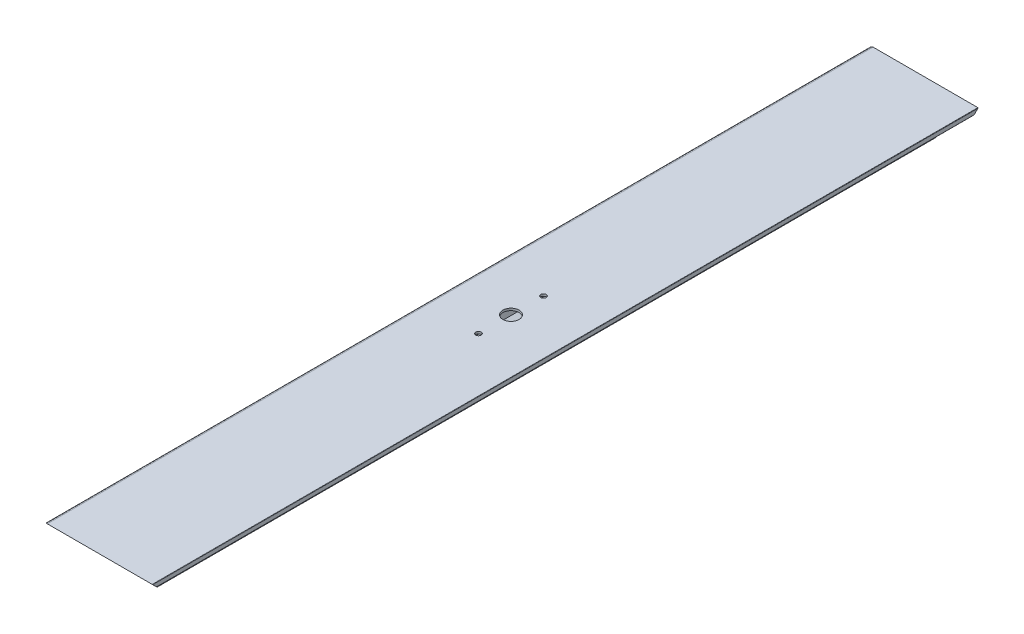
SolidWorks part; units mm, degrees
ref_plane "Front Plane" through (0, 0, 0) normal (0, 0, 1) x (1, 0, 0)
ref_plane "Top Plane" through (0, 0, 0) normal (0, 1, 0) x (1, 0, 0)
ref_plane "Right Plane" through (0, 0, 0) normal (1, 0, 0) x (0, 0, -1)
sketch "Model" plane through (0, 0, 0) normal (0, 0, 1) x (1, 0, 0)
  line L0 (-162.8727, 78.9684) -> (-162.8727, 75.3684)
  line L1 (-97.198, 332.0635) -> (-96.4981, 340.0635)
  line L2 (-92.6351, 332.0635) -> (-97.198, 332.0635)
  line L3 (-97.1625, 332.4695) -> (-95.9741, 333.6579)
  line L4 (-97.0676, 333.5543) -> (-95.8792, 334.7427)
  line L5 (-96.9727, 334.6392) -> (-95.0062, 336.6057)
  line L6 (-96.8777, 335.7241) -> (-95.6894, 336.9124)
  line L7 (-96.7828, 336.8089) -> (-95.5945, 337.9973)
  line L8 (-96.6879, 337.8938) -> (-94.5182, 340.0635)
  line L9 (-120.185, 95.3464) -> (20.315, 95.3464)
  line L10 (20.315, 85.3464) -> (-120.185, 85.3464)
  line L11 (-173.435, 75.3464) -> (20.315, 75.3464)
  line L12 (20.315, 105.3464) -> (-173.435, 105.3464)
  line L13 (-173.435, 342.7864) -> (20.315, 342.7864)
  line L14 (20.315, 85.0964) -> (-120.185, 85.0964)
  line L15 (-120.185, 95.0964) -> (20.315, 95.0964)
  line L16 (-120.185, 105.0964) -> (20.315, 105.0964)
  line L17 (-173.435, 330.0364) -> (20.315, 330.0364)
  line L18 (-82.355, 62.0364) -> (-173.435, 62.0364)
  line L19 (-82.355, 75.0964) -> (-173.435, 75.0964)
  line L20 (-173.435, 62.0364) -> (-173.435, 342.7864)
  line L21 (-173.435, 105.0964) -> (-120.185, 105.0964)
  line L22 (-120.435, 105.3464) -> (-120.435, 75.0964)
  line L23 (-120.185, 95.0964) -> (-120.185, 85.0964)
  line L24 (-120.185, 85.0964) -> (-120.185, 75.0964)
  line L25 (-120.185, 105.0964) -> (-120.185, 95.0964)
  line L26 (-135.8829, 332.0772) -> (-133.6922, 334.2679)
  line L27 (-136.8281, 332.122) -> (-135.9914, 332.9587)
  line L28 (-138.513, 334.4856) -> (-137.6233, 334.4856)
  line L29 (-138.0471, 332.8829) -> (-137.3837, 333.5463)
  line L30 (-138.3972, 333.5227) -> (-137.6286, 334.2914)
  line L31 (-137.8451, 337.0447) -> (-137.151, 337.7388)
  line L32 (-138.0802, 337.7995) -> (-135.8255, 340.0542)
  line L33 (-138.5201, 334.3898) -> (-138.4243, 334.4856)
  line L34 (-134.4764, 338.4335) -> (-133.7983, 339.1117)
  line L35 (-134.9397, 338.9602) -> (-134.2749, 339.6249)
  line L36 (-135.3098, 335.4283) -> (-137.1787, 336.4102)
  line L37 (-136.7085, 337.2046) -> (-134.8554, 336.2311)
  line L38 (-136.0846, 335.8354) -> (-135.4018, 336.5182)
  line L39 (-136.0607, 332.9602) -> (-136.0367, 332.9596)
  line L40 (-136.0968, 332.9586) -> (-136.0607, 332.9602)
  line L41 (-137.5265, 332.4136) -> (-136.8485, 333.0915)
  line L42 (-136.7336, 336.1763) -> (-136.0508, 336.8591)
  line L43 (-137.3711, 336.5287) -> (-136.6998, 337.2)
  line L44 (-135.2783, 335.4135) -> (-135.3098, 335.4283)
  line L45 (-133.4601, 337.7152) -> (-134.3499, 337.7152)
  line L46 (-134.5809, 334.3692) -> (-133.8142, 335.1359)
  line L47 (-134.8458, 335.0942) -> (-134.1871, 335.7529)
  line L48 (-135.4356, 335.4944) -> (-134.7486, 336.1814)
  line L49 (-134.2047, 337.7152) -> (-133.5051, 338.4148)
  line L50 (-135.7157, 339.1741) -> (-134.9284, 339.9614)
  line L51 (-136.0196, 339.1378) -> (-136.079, 339.1324)
  line L52 (-135.9604, 339.1472) -> (-136.0196, 339.1378)
  line L53 (-107.3609, 332.0635) -> (-106.661, 340.0635)
  line L54 (-106.0574, 334.5678) -> (-106.2765, 332.0635)
  line L55 (-102.5158, 332.0635) -> (-104.0259, 334.5678)
  line L56 (-102.7955, 334.7127) -> (-101.198, 332.0635)
  line L57 (-117.9979, 332.0635) -> (-117.298, 340.0635)
  line L58 (-116.611, 335.5213) -> (-116.9135, 332.0635)
  line L59 (-112.4453, 332.0635) -> (-112.1428, 335.5213)
  line L60 (-110.661, 340.0635) -> (-111.3609, 332.0635)
  line L61 (-101.7917, 332.0635) -> (-101.4213, 332.4339)
  line L62 (-102.6158, 332.2294) -> (-101.7937, 333.0514)
  line L63 (-106.7414, 332.0635) -> (-106.232, 332.573)
  line L64 (-124.9402, 332.1742) -> (-121.9937, 335.1207)
  line L65 (-126.0381, 332.0663) -> (-124.7819, 333.3225)
  line L66 (-126.8973, 332.197) -> (-125.9425, 333.1518)
  line L67 (-112.4287, 332.0635) -> (-111.2586, 333.2336)
  line L68 (-117.3784, 332.0635) -> (-116.869, 332.573)
  line L69 (-116.9135, 332.0635) -> (-117.9979, 332.0635)
  line L70 (-111.3609, 332.0635) -> (-112.4453, 332.0635)
  line L71 (-111.4387, 332.0635) -> (-111.3535, 332.1488)
  line L72 (-106.2765, 332.0635) -> (-107.3609, 332.0635)
  line L73 (-101.198, 332.0635) -> (-102.5158, 332.0635)
  line L74 (-116.5161, 336.6057) -> (-112.048, 336.6057)
  line L75 (-112.1428, 335.5213) -> (-116.611, 335.5213)
  line L76 (-115.9005, 335.5213) -> (-114.8161, 336.6057)
  line L77 (-124.2639, 338.7902) -> (-123.4199, 339.6342)
  line L78 (-128.7127, 333.3515) -> (-127.9075, 334.1566)
  line L79 (-129.112, 333.9421) -> (-128.2679, 334.7862)
  line L80 (-129.3993, 334.6447) -> (-128.4536, 335.5904)
  line L81 (-129.5441, 335.4898) -> (-128.3208, 336.7132)
  line L82 (-129.46, 336.564) -> (-126.0538, 339.9701)
  line L83 (-125.0722, 338.9718) -> (-124.1269, 339.9172)
  line L84 (-126.1994, 338.8346) -> (-124.9757, 340.0583)
  line L85 (-127.6117, 332.4726) -> (-126.7637, 333.3205)
  line L86 (-128.2122, 332.8619) -> (-127.4061, 333.668)
  line L87 (-123.6305, 338.4336) -> (-122.8256, 339.2386)
  line L88 (-122.8588, 335.1207) -> (-121.7305, 335.1207)
  line L89 (-121.5655, 337.0064) -> (-122.6938, 337.0064)
  line L90 (-122.0879, 337.0064) -> (-121.6581, 337.4362)
  line L91 (-122.786, 337.2982) -> (-121.938, 338.1462)
  line L92 (-123.1373, 337.9369) -> (-122.3311, 338.7431)
  line L93 (-116.2136, 340.0635) -> (-116.5161, 336.6057)
  line L94 (-117.4879, 337.8938) -> (-116.2995, 339.0822)
  line L95 (-117.3929, 338.9787) -> (-116.3081, 340.0635)
  line L96 (-117.9624, 332.4695) -> (-116.774, 333.6579)
  line L97 (-117.8675, 333.5543) -> (-116.6791, 334.7427)
  line L98 (-117.7726, 334.6392) -> (-115.8061, 336.6057)
  line L99 (-117.6777, 335.7241) -> (-116.4893, 336.9124)
  line L100 (-117.5828, 336.8089) -> (-116.3944, 337.9973)
  line L101 (-117.298, 340.0635) -> (-116.2136, 340.0635)
  line L102 (-105.6715, 338.9791) -> (-105.9639, 335.6368)
  line L103 (-105.9639, 335.6368) -> (-103.6409, 335.6368)
  line L104 (-104.0259, 334.5678) -> (-106.0574, 334.5678)
  line L105 (-106.661, 340.0635) -> (-103.2536, 340.0635)
  line L106 (-107.2305, 333.5543) -> (-105.1481, 335.6368)
  line L107 (-106.9458, 336.8089) -> (-105.7574, 337.9973)
  line L108 (-106.8509, 337.8938) -> (-104.6812, 340.0635)
  line L109 (-106.7559, 338.9787) -> (-105.6711, 340.0635)
  line L110 (-112.048, 336.6057) -> (-111.7454, 340.0635)
  line L111 (-111.8775, 338.5544) -> (-110.6891, 339.7428)
  line L112 (-112.9307, 335.5213) -> (-110.8789, 337.5731)
  line L113 (-113.9206, 335.5213) -> (-112.8362, 336.6057)
  line L114 (-114.9106, 335.5213) -> (-113.8262, 336.6057)
  line L115 (-112.352, 333.1301) -> (-111.1637, 334.3185)
  line L116 (-112.2571, 334.215) -> (-111.0687, 335.4034)
  line L117 (-112.1622, 335.2999) -> (-110.9738, 336.4882)
  line L118 (-111.9724, 337.4696) -> (-110.784, 338.658)
  line L119 (-111.7454, 340.0635) -> (-110.661, 340.0635)
  line L120 (-111.7825, 339.6393) -> (-111.3583, 340.0635)
  line L121 (-107.3254, 332.4695) -> (-106.1371, 333.6579)
  line L122 (-107.1356, 334.6392) -> (-105.9472, 335.8276)
  line L123 (-107.0407, 335.7241) -> (-105.8523, 336.9124)
  line L124 (-103.733, 334.082) -> (-100.7764, 337.0386)
  line L125 (-101.9127, 336.8923) -> (-100.7724, 338.0326)
  line L126 (-101.8837, 337.9112) -> (-101.029, 338.7659)
  line L127 (-102.2514, 338.5335) -> (-101.4504, 339.3345)
  line L128 (-102.8681, 338.9067) -> (-102.0179, 339.7569)
  line L129 (-103.7857, 338.9791) -> (-102.748, 340.0168)
  line L130 (-104.7756, 338.9791) -> (-103.6912, 340.0635)
  line L131 (-103.3485, 338.9791) -> (-105.6715, 338.9791)
  line L132 (-104.2371, 334.5678) -> (-103.0712, 335.7337)
  line L133 (-105.2271, 334.5678) -> (-104.1581, 335.6368)
  line L134 (-102.9882, 332.8469) -> (-102.1661, 333.669)
  line L135 (-103.3606, 333.4645) -> (-102.5385, 334.2865)
  line L136 (20.315, 342.7864) -> (20.315, 62.0364)
  line L137 (20.315, 62.0364) -> (-82.355, 62.0364)
  line L138 (-82.355, 75.0964) -> (20.315, 75.0964)
  line L139 (-33.435, 105.0964) -> (-33.435, 62.0364)
  line L140 (-76.935, 105.0964) -> (-76.935, 62.0364)
  line L141 (-76.685, 62.0364) -> (-76.685, 75.0964)
  line L142 (-33.185, 62.0364) -> (-33.185, 95.0964)
  line L143 (-76.685, 95.0964) -> (-76.685, 75.0964)
  line L144 (-76.685, 95.0964) -> (-76.685, 105.0964)
  line L145 (-33.185, 95.0964) -> (-33.185, 105.0964)
  line L146 (-69.6745, 332.0635) -> (-68.9746, 340.0635)
  line L147 (-68.371, 334.5678) -> (-68.5901, 332.0635)
  line L148 (-64.8294, 332.0635) -> (-66.3395, 334.5678)
  line L149 (-65.1091, 334.7127) -> (-63.5116, 332.0635)
  line L150 (-78.2374, 332.0635) -> (-77.5375, 340.0635)
  line L151 (-73.5796, 333.1479) -> (-73.6745, 332.0635)
  line L152 (-88.6351, 332.0635) -> (-87.9352, 340.0635)
  line L153 (-87.1624, 336.5009) -> (-87.5507, 332.0635)
  line L154 (-86.0396, 332.0635) -> (-87.1624, 336.5009)
  line L155 (-82.9336, 336.5009) -> (-84.8329, 332.0635)
  line L156 (-83.3218, 332.0635) -> (-82.9336, 336.5009)
  line L157 (-81.5375, 340.0635) -> (-82.2374, 332.0635)
  line L158 (-92.5402, 333.1479) -> (-92.6351, 332.0635)
  line L159 (-64.1052, 332.0635) -> (-63.7349, 332.4339)
  line L160 (-64.9294, 332.2294) -> (-64.1073, 333.0514)
  line L161 (-69.055, 332.0635) -> (-68.5455, 332.573)
  line L162 (-93.6086, 332.0635) -> (-92.5417, 333.1304)
  line L163 (-94.5986, 332.0635) -> (-93.5142, 333.1479)
  line L164 (-95.5885, 332.0635) -> (-94.5041, 333.1479)
  line L165 (-96.5785, 332.0635) -> (-95.4941, 333.1479)
  line L166 (-74.6481, 332.0635) -> (-73.5811, 333.1304)
  line L167 (-75.638, 332.0635) -> (-74.5536, 333.1479)
  line L168 (-76.628, 332.0635) -> (-75.5436, 333.1479)
  line L169 (-77.6179, 332.0635) -> (-76.5335, 333.1479)
  line L170 (-83.0658, 332.0635) -> (-82.158, 332.9713)
  line L171 (-85.0457, 332.0635) -> (-84.6736, 332.4356)
  line L172 (-86.0357, 332.0635) -> (-83.9328, 334.1664)
  line L173 (-88.0156, 332.0635) -> (-87.5061, 332.573)
  line L174 (-87.5507, 332.0635) -> (-88.6351, 332.0635)
  line L175 (-82.2374, 332.0635) -> (-83.3218, 332.0635)
  line L176 (-84.8329, 332.0635) -> (-86.0396, 332.0635)
  line L177 (-68.5901, 332.0635) -> (-69.6745, 332.0635)
  line L178 (-73.6745, 332.0635) -> (-78.2374, 332.0635)
  line L179 (-63.5116, 332.0635) -> (-64.8294, 332.0635)
  line L180 (-87.9352, 340.0635) -> (-86.9184, 340.0635)
  line L181 (-88.5995, 332.4695) -> (-87.4112, 333.6579)
  line L182 (-88.5046, 333.5543) -> (-87.3163, 334.7427)
  line L183 (-88.4097, 334.6392) -> (-87.2213, 335.8276)
  line L184 (-88.3148, 335.7241) -> (-86.3241, 337.7148)
  line L185 (-88.2199, 336.8089) -> (-86.524, 338.5048)
  line L186 (-88.125, 337.8938) -> (-86.7239, 339.2949)
  line L187 (-88.0301, 338.9787) -> (-86.9452, 340.0635)
  line L188 (-92.03, 338.9791) -> (-95.5086, 338.9791)
  line L189 (-96.4981, 340.0635) -> (-91.9352, 340.0635)
  line L190 (-92.6327, 338.9791) -> (-91.9722, 339.6396)
  line L191 (-93.6227, 338.9791) -> (-92.5383, 340.0635)
  line L192 (-94.6126, 338.9791) -> (-93.5282, 340.0635)
  line L193 (-96.593, 338.9787) -> (-95.5081, 340.0635)
  line L194 (-96.0187, 333.1479) -> (-92.5402, 333.1479)
  line L195 (-92.3325, 335.5213) -> (-95.8111, 335.5213)
  line L196 (-95.7162, 336.6057) -> (-92.2377, 336.6057)
  line L197 (-95.1006, 335.5213) -> (-94.0162, 336.6057)
  line L198 (-95.8111, 335.5213) -> (-96.0187, 333.1479)
  line L199 (-95.5086, 338.9791) -> (-95.7162, 336.6057)
  line L200 (-92.2377, 336.6057) -> (-92.3325, 335.5213)
  line L201 (-93.1207, 335.5213) -> (-92.257, 336.385)
  line L202 (-94.1107, 335.5213) -> (-93.0263, 336.6057)
  line L203 (-91.9352, 340.0635) -> (-92.03, 338.9791)
  line L204 (-85.2969, 333.6557) -> (-82.5543, 340.0635)
  line L205 (-83.2515, 332.8678) -> (-82.0631, 334.0562)
  line L206 (-83.1565, 333.9527) -> (-81.9682, 335.1411)
  line L207 (-83.0616, 335.0376) -> (-81.8733, 336.2259)
  line L208 (-82.9667, 336.1224) -> (-81.7783, 337.3108)
  line L209 (-84.454, 335.6251) -> (-81.6834, 338.3956)
  line L210 (-83.7132, 337.3558) -> (-81.5885, 339.4805)
  line L211 (-82.9724, 339.0866) -> (-81.9955, 340.0635)
  line L212 (-86.9184, 340.0635) -> (-85.2969, 333.6557)
  line L213 (-86.2387, 332.8504) -> (-85.3245, 333.7646)
  line L214 (-86.4386, 333.6405) -> (-85.5244, 334.5547)
  line L215 (-86.6385, 334.4305) -> (-85.7243, 335.3447)
  line L216 (-86.8385, 335.2205) -> (-85.9242, 336.1347)
  line L217 (-87.0384, 336.0106) -> (-86.1242, 336.9248)
  line L218 (-85.1948, 333.8943) -> (-83.192, 335.8971)
  line L219 (-82.5543, 340.0635) -> (-81.5375, 340.0635)
  line L220 (-69.639, 332.4695) -> (-68.4506, 333.6579)
  line L221 (-69.5441, 333.5543) -> (-67.4616, 335.6368)
  line L222 (-69.4491, 334.6392) -> (-68.2608, 335.8276)
  line L223 (-69.3542, 335.7241) -> (-68.1659, 336.9124)
  line L224 (-69.2593, 336.8089) -> (-68.071, 337.9973)
  line L225 (-77.0581, 333.1479) -> (-73.5796, 333.1479)
  line L226 (-73.372, 335.5213) -> (-76.8505, 335.5213)
  line L227 (-76.7556, 336.6057) -> (-73.2771, 336.6057)
  line L228 (-73.0695, 338.9791) -> (-76.548, 338.9791)
  line L229 (-77.5375, 340.0635) -> (-72.9746, 340.0635)
  line L230 (-74.1602, 335.5213) -> (-73.2964, 336.385)
  line L231 (-74.6621, 338.9791) -> (-73.5777, 340.0635)
  line L232 (-75.6521, 338.9791) -> (-74.5677, 340.0635)
  line L233 (-77.7273, 337.8938) -> (-75.5576, 340.0635)
  line L234 (-77.6324, 338.9787) -> (-76.5476, 340.0635)
  line L235 (-76.14, 335.5213) -> (-75.0556, 336.6057)
  line L236 (-78.0121, 334.6392) -> (-76.0456, 336.6057)
  line L237 (-76.8505, 335.5213) -> (-77.0581, 333.1479)
  line L238 (-76.548, 338.9791) -> (-76.7556, 336.6057)
  line L239 (-78.2019, 332.4695) -> (-77.0135, 333.6579)
  line L240 (-78.107, 333.5543) -> (-76.9186, 334.7427)
  line L241 (-77.9172, 335.7241) -> (-76.7288, 336.9124)
  line L242 (-77.8223, 336.8089) -> (-76.6339, 337.9973)
  line L243 (-75.1501, 335.5213) -> (-74.0657, 336.6057)
  line L244 (-72.9746, 340.0635) -> (-73.0695, 338.9791)
  line L245 (-73.6722, 338.9791) -> (-73.0117, 339.6396)
  line L246 (-73.2771, 336.6057) -> (-73.372, 335.5213)
  line L247 (-65.3017, 332.8469) -> (-64.4797, 333.669)
  line L248 (-66.0465, 334.082) -> (-63.0899, 337.0386)
  line L249 (-65.1817, 338.9067) -> (-64.3314, 339.7569)
  line L250 (-66.0992, 338.9791) -> (-65.0615, 340.0168)
  line L251 (-67.0892, 338.9791) -> (-66.0048, 340.0635)
  line L252 (-69.1644, 337.8938) -> (-66.9947, 340.0635)
  line L253 (-69.0695, 338.9787) -> (-67.9846, 340.0635)
  line L254 (-65.6621, 338.9791) -> (-67.9851, 338.9791)
  line L255 (-68.2775, 335.6368) -> (-65.9545, 335.6368)
  line L256 (-66.3395, 334.5678) -> (-68.371, 334.5678)
  line L257 (-67.5406, 334.5678) -> (-66.4717, 335.6368)
  line L258 (-67.9851, 338.9791) -> (-68.2775, 335.6368)
  line L259 (-65.6741, 333.4645) -> (-64.8521, 334.2865)
  line L260 (-66.5507, 334.5678) -> (-65.3848, 335.7337)
  line L261 (-68.9746, 340.0635) -> (-65.5672, 340.0635)
  line L262 (-64.565, 338.5335) -> (-63.7639, 339.3345)
  line L263 (-64.2263, 336.8923) -> (-63.086, 338.0326)
  line L264 (-64.1972, 337.9112) -> (-63.3425, 338.7659)
  line L265 (-33.235, 330.0364) -> (-33.235, 343.0364)
  line L266 (-122.3762, 215.7611) -> (-104.8919, 215.7611)
  line L267 (-104.8919, 215.7611) -> (-94.8762, 221.9241)
  line L268 (-94.8762, 221.9241) -> (-94.8762, 234.4611)
  line L269 (-95.1762, 234.7611) -> (-122.3762, 234.7611)
  line L270 (-123.8762, 233.2611) -> (-123.8762, 217.2611)
  line L271 (-83.3762, 213.7611) -> (-47.8762, 213.7611)
  line L272 (-44.8762, 216.7611) -> (-44.8762, 232.4611)
  line L273 (-44.5762, 232.7611) -> (-28.1762, 232.7611)
  line L274 (-27.8762, 233.0611) -> (-27.8762, 236.4611)
  line L275 (-28.1762, 236.7611) -> (-124.8762, 236.7611)
  line L276 (-127.8762, 233.7611) -> (-127.8762, 216.7611)
  line L277 (-124.8762, 213.7611) -> (-102.4177, 213.7611)
  line L278 (-102.4177, 213.7611) -> (-93.4187, 219.2985)
  line L279 (-93.4187, 219.2985) -> (-83.3762, 213.7611)
  line L280 (-82.8614, 215.7611) -> (-50.8762, 215.7611)
  line L281 (-48.8762, 217.7611) -> (-48.8762, 234.4611)
  line L282 (-49.1762, 234.7611) -> (-92.5762, 234.7611)
  line L283 (-92.8762, 234.4611) -> (-92.8762, 221.2832)
  line L284 (-92.8762, 221.2832) -> (-82.8614, 215.7611)
  arc A0 (-137.8968, 332.7133) -> (-137.2797, 332.2779) centre (-136.3771, 334.2121) ccw
  arc A1 (-136.1303, 332.0696) -> (-134.4439, 332.7179) centre (-136.0797, 334.4557) ccw
  arc A2 (-137.2797, 332.2779) -> (-136.1303, 332.0696) centre (-136.3093, 334.3574) ccw
  arc A3 (-137.4521, 339.4174) -> (-138.0003, 338.5211) centre (-135.946, 337.8806) ccw
  arc A4 (-138.0372, 337.5237) -> (-137.1787, 336.4102) centre (-136.3894, 337.9064) ccw
  arc A5 (-138.0003, 338.5211) -> (-138.0372, 337.5237) centre (-136.1826, 337.9544) ccw
  arc A6 (-138.513, 334.4856) -> (-138.3231, 333.3359) centre (-136.2433, 334.2702) ccw
  arc A7 (-138.3231, 333.3359) -> (-137.8968, 332.7133) centre (-136.381, 334.2083) ccw
  arc A8 (-136.1086, 339.1312) -> (-136.8552, 338.8092) centre (-136.0647, 338.0029) ccw
  arc A9 (-134.7814, 338.8399) -> (-135.2015, 339.09) centre (-135.6424, 337.8715) ccw
  arc A10 (-133.6796, 338.9039) -> (-134.1549, 339.526) centre (-135.521, 337.9895) ccw
  arc A11 (-136.0367, 332.9596) -> (-135.033, 333.3339) centre (-135.9879, 334.3617) ccw
  arc A12 (-136.8315, 333.0836) -> (-136.0968, 332.9586) centre (-136.2282, 334.4081) ccw
  arc A13 (-137.2271, 333.358) -> (-136.8315, 333.0836) centre (-136.2714, 334.3133) ccw
  arc A14 (-137.5008, 333.7533) -> (-137.2271, 333.358) centre (-136.2749, 334.3098) ccw
  arc A15 (-137.6233, 334.4856) -> (-137.5008, 333.7533) centre (-136.1881, 334.3492) ccw
  arc A16 (-137.1671, 337.7985) -> (-136.7085, 337.2046) centre (-136.2881, 338.0032) ccw
  arc A17 (-137.1476, 338.3307) -> (-137.1671, 337.7985) centre (-136.1779, 338.0288) ccw
  arc A18 (-136.8552, 338.8092) -> (-137.1476, 338.3307) centre (-136.0516, 337.9895) ccw
  arc A19 (-134.6244, 334.6679) -> (-135.2783, 335.4135) centre (-135.7117, 334.3738) ccw
  arc A20 (-134.6369, 333.9643) -> (-134.6244, 334.6679) centre (-135.8451, 334.3378) ccw
  arc A21 (-135.033, 333.3339) -> (-134.6369, 333.9643) centre (-136.0142, 334.39) ccw
  arc A22 (-134.4439, 332.7179) -> (-133.7816, 333.7826) centre (-136.1206, 334.4991) ccw
  arc A23 (-133.7816, 333.7826) -> (-133.7607, 334.968) centre (-135.8351, 334.4117) ccw
  arc A24 (-133.7607, 334.968) -> (-134.8554, 336.2311) centre (-135.6087, 334.4724) ccw
  arc A25 (-134.4862, 338.4535) -> (-134.7814, 338.8399) centre (-135.6299, 337.8856) ccw
  arc A26 (-134.3499, 337.7152) -> (-134.4862, 338.4535) centre (-135.7099, 337.8458) ccw
  arc A27 (-133.4601, 337.7152) -> (-133.6796, 338.9039) centre (-135.6498, 337.9255) ccw
  arc A28 (-135.2015, 339.09) -> (-135.9604, 339.1472) centre (-135.6834, 337.7581) ccw
  arc A29 (-134.8312, 339.9286) -> (-136.0531, 340.0207) centre (-135.6072, 337.7842) ccw
  arc A30 (-136.0531, 340.0207) -> (-137.4521, 339.4174) centre (-135.9707, 337.9058) ccw
  arc A31 (-136.1086, 339.1312) -> (-136.079, 339.1324) centre (-136.1063, 339.4324) ccw
  arc A32 (-134.1549, 339.526) -> (-134.8312, 339.9286) centre (-135.5411, 337.9668) ccw
  arc A33 (-128.6111, 333.2351) -> (-127.1113, 332.2618) centre (-125.9783, 335.6497) ccw
  arc A34 (-124.6395, 332.2569) -> (-122.9543, 333.2351) centre (-125.985, 336.5157) ccw
  arc A35 (-127.1113, 332.2618) -> (-125.8936, 332.0635) centre (-125.8936, 335.9029) ccw
  arc A36 (-125.8936, 332.0635) -> (-124.6395, 332.2569) centre (-125.8936, 336.2265) ccw
  arc A37 (-124.8823, 333.2889) -> (-123.654, 334.0019) centre (-125.8631, 336.3931) ccw
  arc A38 (-123.2933, 338.1252) -> (-124.3865, 338.8346) centre (-125.2123, 336.3651) ccw
  arc A39 (-123.9592, 339.8653) -> (-125.1769, 340.0635) centre (-125.1769, 336.2241) ccw
  arc A40 (-128.1162, 338.892) -> (-128.7635, 338.1528) centre (-125.0399, 335.5451) ccw
  arc A41 (-129.1281, 333.9724) -> (-128.6111, 333.2351) centre (-126, 335.6157) ccw
  arc A42 (-128.7635, 338.1528) -> (-129.0975, 337.5931) centre (-125.1016, 335.5884) ccw
  arc A43 (-129.0975, 337.5931) -> (-129.3438, 336.995) centre (-125.1996, 335.6375) ccw
  arc A44 (-129.3438, 336.995) -> (-129.5353, 336.0635) centre (-125.3666, 335.6922) ccw
  arc A45 (-129.5353, 336.0635) -> (-129.506, 335.1272) centre (-125.6446, 335.7165) ccw
  arc A46 (-129.506, 335.1272) -> (-129.3642, 334.5313) centre (-125.818, 335.69) ccw
  arc A47 (-129.3642, 334.5313) -> (-129.1281, 333.9724) centre (-125.9252, 335.655) ccw
  arc A48 (-126.431, 339.8701) -> (-128.1162, 338.892) centre (-125.0855, 335.6113) ccw
  arc A49 (-126.6841, 333.2924) -> (-125.7965, 333.1479) centre (-125.7965, 335.9465) ccw
  arc A50 (-126.1882, 338.8382) -> (-127.4165, 338.1252) centre (-125.2074, 335.7339) ccw
  arc A51 (-127.7773, 334.0019) -> (-126.6841, 333.2924) centre (-125.8582, 335.7619) ccw
  arc A52 (-128.1541, 334.5393) -> (-127.7773, 334.0019) centre (-125.874, 335.7371) ccw
  arc A53 (-128.3262, 334.9467) -> (-128.1541, 334.5393) centre (-125.8195, 335.7657) ccw
  arc A54 (-128.4295, 335.3811) -> (-128.3262, 334.9467) centre (-125.7414, 335.7913) ccw
  arc A55 (-128.4509, 336.0635) -> (-128.4295, 335.3811) centre (-125.615, 335.8106) ccw
  arc A56 (-128.3113, 336.7425) -> (-128.4509, 336.0635) centre (-125.4123, 335.7929) ccw
  arc A57 (-128.1317, 337.1784) -> (-128.3113, 336.7425) centre (-125.2906, 335.753) ccw
  arc A58 (-127.8883, 337.5864) -> (-128.1317, 337.1784) centre (-125.2192, 335.7172) ccw
  arc A59 (-127.4165, 338.1252) -> (-127.8883, 337.5864) centre (-125.1742, 335.6857) ccw
  arc A60 (-125.7965, 333.1479) -> (-124.8823, 333.2889) centre (-125.7965, 336.1823) ccw
  arc A61 (-125.274, 338.9791) -> (-126.1882, 338.8382) centre (-125.274, 335.9447) ccw
  arc A62 (-124.3865, 338.8346) -> (-125.274, 338.9791) centre (-125.274, 336.1806) ccw
  arc A63 (-125.1769, 340.0635) -> (-126.431, 339.8701) centre (-125.1769, 335.9005) ccw
  arc A64 (-122.4594, 338.892) -> (-123.9592, 339.8653) centre (-125.0922, 336.4773) ccw
  arc A65 (-121.991, 334.4986) -> (-121.7305, 335.1207) centre (-125.8787, 336.4924) ccw
  arc A66 (-121.7178, 337.6302) -> (-121.8765, 338.0226) centre (-125.1512, 336.4701) ccw
  arc A67 (-122.9543, 333.2351) -> (-122.4859, 333.7359) centre (-126.037, 336.5879) ccw
  arc A68 (-122.4859, 333.7359) -> (-122.2187, 334.1054) centre (-126.0093, 336.5657) ccw
  arc A69 (-122.2187, 334.1054) -> (-121.991, 334.4986) centre (-125.9635, 336.5359) ccw
  arc A70 (-123.0452, 334.7535) -> (-122.8588, 335.1207) centre (-125.8239, 336.3946) ccw
  arc A71 (-123.1957, 334.5215) -> (-123.0452, 334.7535) centre (-125.8664, 336.4197) ccw
  arc A72 (-123.3657, 334.3025) -> (-123.1957, 334.5215) centre (-125.8889, 336.4357) ccw
  arc A73 (-123.654, 334.0019) -> (-123.3657, 334.3025) centre (-125.9022, 336.4469) ccw
  arc A74 (-123.0577, 337.8248) -> (-123.2933, 338.1252) centre (-125.1879, 336.3967) ccw
  arc A75 (-122.9261, 337.6059) -> (-123.0577, 337.8248) centre (-125.2067, 336.384) ccw
  arc A76 (-122.8163, 337.3743) -> (-122.9261, 337.6059) centre (-125.2336, 336.3696) ccw
  arc A77 (-122.6938, 337.0064) -> (-122.8163, 337.3743) centre (-125.2811, 336.3499) ccw
  arc A78 (-121.8765, 338.0226) -> (-122.079, 338.3918) centre (-125.0983, 336.4952) ccw
  arc A79 (-122.079, 338.3918) -> (-122.4594, 338.892) centre (-125.0614, 336.5184) ccw
  arc A80 (-121.5655, 337.0064) -> (-121.7178, 337.6302) centre (-125.2435, 336.4389) ccw
  arc A81 (-101.3807, 335.7211) -> (-101.0093, 336.3186) centre (-103.8062, 337.643) ccw
  arc A82 (-100.9324, 338.5637) -> (-101.376, 339.2565) centre (-103.1704, 337.6191) ccw
  arc A83 (-102.6033, 338.7954) -> (-103.3485, 338.9791) centre (-103.3381, 337.4175) ccw
  arc A84 (-103.6409, 335.6368) -> (-102.869, 335.8174) centre (-103.6516, 337.4219) ccw
  arc A85 (-102.2098, 338.4897) -> (-102.6033, 338.7954) centre (-103.2939, 337.5005) ccw
  arc A86 (-101.9407, 338.0695) -> (-102.2098, 338.4897) centre (-103.298, 337.4967) ccw
  arc A87 (-101.8236, 337.3079) -> (-101.9407, 338.0695) centre (-103.3942, 337.4561) ccw
  arc A88 (-102.0705, 336.5516) -> (-101.8236, 337.3079) centre (-103.6177, 337.4752) ccw
  arc A89 (-102.4165, 336.1261) -> (-102.0705, 336.5516) centre (-103.705, 337.5274) ccw
  arc A90 (-102.869, 335.8174) -> (-102.4165, 336.1261) centre (-103.7008, 337.5228) ccw
  arc A91 (-102.7955, 334.7127) -> (-101.8796, 335.2196) centre (-103.8132, 337.6329) ccw
  arc A92 (-101.8796, 335.2196) -> (-101.3807, 335.7211) centre (-103.8475, 337.6757) ccw
  arc A93 (-101.376, 339.2565) -> (-102.0248, 339.7606) centre (-103.1635, 337.6254) ccw
  arc A94 (-102.0248, 339.7606) -> (-103.2536, 340.0635) centre (-103.2365, 337.4885) ccw
  arc A95 (-101.0093, 336.3186) -> (-100.7392, 337.3079) centre (-103.6612, 337.5743) ccw
  arc A96 (-100.7392, 337.3079) -> (-100.9324, 338.5637) centre (-103.3289, 337.5522) ccw
  arc A97 (-64.5233, 338.4897) -> (-64.9168, 338.7954) centre (-65.6074, 337.5005) ccw
  arc A98 (-64.7301, 336.1261) -> (-64.3841, 336.5516) centre (-66.0186, 337.5274) ccw
  arc A99 (-65.1091, 334.7127) -> (-64.1931, 335.2196) centre (-66.1268, 337.6329) ccw
  arc A100 (-64.3384, 339.7606) -> (-65.5672, 340.0635) centre (-65.5501, 337.4885) ccw
  arc A101 (-64.9168, 338.7954) -> (-65.6621, 338.9791) centre (-65.6517, 337.4175) ccw
  arc A102 (-65.1825, 335.8174) -> (-64.7301, 336.1261) centre (-66.0144, 337.5228) ccw
  arc A103 (-65.9545, 335.6368) -> (-65.1825, 335.8174) centre (-65.9652, 337.4219) ccw
  arc A104 (-63.2459, 338.5637) -> (-63.6896, 339.2565) centre (-65.484, 337.6191) ccw
  arc A105 (-64.2543, 338.0695) -> (-64.5233, 338.4897) centre (-65.6116, 337.4967) ccw
  arc A106 (-64.1371, 337.3079) -> (-64.2543, 338.0695) centre (-65.7077, 337.4561) ccw
  arc A107 (-64.3841, 336.5516) -> (-64.1371, 337.3079) centre (-65.9313, 337.4752) ccw
  arc A108 (-64.1931, 335.2196) -> (-63.6943, 335.7211) centre (-66.1611, 337.6757) ccw
  arc A109 (-63.6943, 335.7211) -> (-63.3229, 336.3186) centre (-66.1197, 337.643) ccw
  arc A110 (-63.3229, 336.3186) -> (-63.0527, 337.3079) centre (-65.9748, 337.5743) ccw
  arc A111 (-63.0527, 337.3079) -> (-63.2459, 338.5637) centre (-65.6425, 337.5522) ccw
  arc A112 (-63.6896, 339.2565) -> (-64.3384, 339.7606) centre (-65.4771, 337.6254) ccw
  arc A113 (-94.8762, 234.4611) -> (-95.1762, 234.7611) centre (-95.1762, 234.4611) ccw
  arc A114 (-122.3762, 234.7611) -> (-123.8762, 233.2611) centre (-122.3762, 233.2611) ccw
  arc A115 (-123.8762, 217.2611) -> (-122.3762, 215.7611) centre (-122.3762, 217.2611) ccw
  arc A116 (-47.8762, 213.7611) -> (-44.8762, 216.7611) centre (-47.8762, 216.7611) ccw
  arc A117 (-44.5762, 232.7611) -> (-44.8762, 232.4611) centre (-44.5762, 232.4611) ccw
  arc A118 (-28.1762, 232.7611) -> (-27.8762, 233.0611) centre (-28.1762, 233.0611) ccw
  arc A119 (-27.8762, 236.4611) -> (-28.1762, 236.7611) centre (-28.1762, 236.4611) ccw
  arc A120 (-124.8762, 236.7611) -> (-127.8762, 233.7611) centre (-124.8762, 233.7611) ccw
  arc A121 (-127.8762, 216.7611) -> (-124.8762, 213.7611) centre (-124.8762, 216.7611) ccw
  arc A122 (-50.8762, 215.7611) -> (-48.8762, 217.7611) centre (-50.8762, 217.7611) ccw
  arc A123 (-48.8762, 234.4611) -> (-49.1762, 234.7611) centre (-49.1762, 234.4611) ccw
  arc A124 (-92.5762, 234.7611) -> (-92.8762, 234.4611) centre (-92.5762, 234.4611) ccw
  text T0 "*" font "SWTXT" height 4
  text T1 "ALLOY 6063T5, ALLOY 6060T5" font "SWTXT" height 2.4
  text T2 "A.F." font "SWTXT" height 4
  text T3 "04-11-07" font "SWTXT" height 4
  text T4 "GENERAL TOLERANCES" font "SWTXT" height 2.5
  text T5 "F RAD  =" font "SWTXT" height 2.5
  text T6 "V =" font "SWTXT" height 2.5
  text T7 "B RADS =" font "SWTXT" height 2.5
  text T8 "A RADS =" font "SWTXT" height 2.5
  text T9 "mm" font "SWTXT" height 2.5
  text T10 "mm" font "SWTXT" height 2.5
  text T11 "mm" font "SWTXT" height 2.5
  text T12 "I.D.GROOVE" font "SWTXT" height 2.5
  text T13 "FULL RAD" font "SWTXT" height 2.5
  text T14 "DIN 17615" font "SWTXT" height 4
  text T15 "DRAWN" font "SWTXT" height 2.5
  text T16 "DATE" font "SWTXT" height 2.5
  text T17 "BOLSTER No." font "SWTXT" height 2.5
  text T18 "MATERIAL" font "SWTXT" height 2.5
  text T19 "SCALE" font "SWTXT" height 2.5
  text T20 "GEN WALL" font "SWTXT" height 2.5
  text T21 "UNSTATED RADS" font "SWTXT" height 2.5
  text T22 "591.87" font "SWTXT" height 4
  text T23 "PERIMETER" font "SWTXT" height 2.5
  text T24 "WEIGHT" font "SWTXT" height 2.5
  text T25 "AREA" font "SWTXT" height 2.5
  text T26 "No. CAVS" font "SWTXT" height 2.5
  text T27 "mm" font "SWTXT" height 2.5
  text T28 "kg/m" font "SWTXT" height 2.5
  text T29 "1.598" font "SWTXT" height 4
  text T30 "2" font "SWTXT" height 1.875
  text T31 "1:1" font "SWTXT" height 4
  text T32 "mm" font "SWTXT" height 2.5
  text T33 "mm" font "SWTXT" height 2.5
  text T34 "SECT No." font "SWTXT" height 2.5
  text T35 "6194B" font "SWTXT" height 4
  text T36 "0.3" font "SWTXT" height 4
  text T37 "EXT.244.74mm" font "SWTXT" height 3.2
  text T38 "INT.210.94" font "SWTXT" height 3.2
sketch "Sketch2" plane through (0, 0, 0) normal (0, 0, 1) x (1, 0, 0)
  line L0 (-49.1762, 234.7611) -> (-92.5762, 234.7611) construction
  line L1 (-92.8762, 234.4611) -> (-92.8762, 221.2832) construction
  line L2 (-92.8762, 221.2832) -> (-82.8614, 215.7611) construction
  line L3 (-82.8614, 215.7611) -> (-50.8762, 215.7611) construction
  line L4 (-48.8762, 217.7611) -> (-48.8762, 234.4611) construction
  line L5 (-28.1762, 236.7611) -> (-124.8762, 236.7611) construction
  line L6 (-127.8762, 233.7611) -> (-127.8762, 216.7611) construction
  line L7 (-124.8762, 213.7611) -> (-102.4177, 213.7611) construction
  line L8 (-102.4177, 213.7611) -> (-93.4187, 219.2985) construction
  line L9 (-93.4187, 219.2985) -> (-83.3762, 213.7611) construction
  line L10 (-83.3762, 213.7611) -> (-47.8762, 213.7611) construction
  line L11 (-44.8762, 216.7611) -> (-44.8762, 232.4611) construction
  line L12 (-44.5762, 232.7611) -> (-28.1762, 232.7611) construction
  line L13 (-27.8762, 233.0611) -> (-27.8762, 236.4611) construction
  line L14 (-95.1762, 234.7611) -> (-122.3762, 234.7611) construction
  line L15 (-123.8762, 233.2611) -> (-123.8762, 217.2611) construction
  line L16 (-122.3762, 215.7611) -> (-104.8919, 215.7611) construction
  line L17 (-104.8919, 215.7611) -> (-94.8762, 221.9241) construction
  line L18 (-94.8762, 221.9241) -> (-94.8762, 234.4611) construction
  line L19 (-49.1762, 234.7611) -> (-92.5762, 234.7611)
  line L20 (-92.8762, 234.4611) -> (-92.8762, 221.2832)
  line L21 (-92.8762, 221.2832) -> (-82.8614, 215.7611)
  line L22 (-82.8614, 215.7611) -> (-50.8762, 215.7611)
  line L23 (-48.8762, 217.7611) -> (-48.8762, 234.4611)
  line L24 (-28.1762, 236.7611) -> (-124.8762, 236.7611)
  line L25 (-127.8762, 233.7611) -> (-127.8762, 216.7611)
  line L26 (-124.8762, 213.7611) -> (-102.4177, 213.7611)
  line L27 (-102.4177, 213.7611) -> (-93.4187, 219.2985)
  line L28 (-93.4187, 219.2985) -> (-83.3762, 213.7611)
  line L29 (-83.3762, 213.7611) -> (-47.8762, 213.7611)
  line L30 (-44.8762, 216.7611) -> (-44.8762, 232.4611)
  line L31 (-44.5762, 232.7611) -> (-28.1762, 232.7611)
  line L32 (-27.8762, 233.0611) -> (-27.8762, 236.4611)
  line L33 (-95.1762, 234.7611) -> (-122.3762, 234.7611)
  line L34 (-123.8762, 233.2611) -> (-123.8762, 217.2611)
  line L35 (-122.3762, 215.7611) -> (-104.8919, 215.7611)
  line L36 (-104.8919, 215.7611) -> (-94.8762, 221.9241)
  line L37 (-94.8762, 221.9241) -> (-94.8762, 234.4611)
  arc A0 (-92.5762, 234.7611) -> (-92.8762, 234.4611) centre (-92.5762, 234.4611) ccw construction
  arc A1 (-50.8762, 215.7611) -> (-48.8762, 217.7611) centre (-50.8762, 217.7611) ccw construction
  arc A2 (-48.8762, 234.4611) -> (-49.1762, 234.7611) centre (-49.1762, 234.4611) ccw construction
  arc A3 (-124.8762, 236.7611) -> (-127.8762, 233.7611) centre (-124.8762, 233.7611) ccw construction
  arc A4 (-127.8762, 216.7611) -> (-124.8762, 213.7611) centre (-124.8762, 216.7611) ccw construction
  arc A5 (-47.8762, 213.7611) -> (-44.8762, 216.7611) centre (-47.8762, 216.7611) ccw construction
  arc A6 (-44.5762, 232.7611) -> (-44.8762, 232.4611) centre (-44.5762, 232.4611) ccw construction
  arc A7 (-28.1762, 232.7611) -> (-27.8762, 233.0611) centre (-28.1762, 233.0611) ccw construction
  arc A8 (-27.8762, 236.4611) -> (-28.1762, 236.7611) centre (-28.1762, 236.4611) ccw construction
  arc A9 (-122.3762, 234.7611) -> (-123.8762, 233.2611) centre (-122.3762, 233.2611) ccw construction
  arc A10 (-123.8762, 217.2611) -> (-122.3762, 215.7611) centre (-122.3762, 217.2611) ccw construction
  arc A11 (-94.8762, 234.4611) -> (-95.1762, 234.7611) centre (-95.1762, 234.4611) ccw construction
  arc A12 (-92.5762, 234.7611) -> (-92.8762, 234.4611) centre (-92.5762, 234.4611) ccw
  arc A13 (-50.8762, 215.7611) -> (-48.8762, 217.7611) centre (-50.8762, 217.7611) ccw
  arc A14 (-48.8762, 234.4611) -> (-49.1762, 234.7611) centre (-49.1762, 234.4611) ccw
  arc A15 (-124.8762, 236.7611) -> (-127.8762, 233.7611) centre (-124.8762, 233.7611) ccw
  arc A16 (-127.8762, 216.7611) -> (-124.8762, 213.7611) centre (-124.8762, 216.7611) ccw
  arc A17 (-47.8762, 213.7611) -> (-44.8762, 216.7611) centre (-47.8762, 216.7611) ccw
  arc A18 (-44.5762, 232.7611) -> (-44.8762, 232.4611) centre (-44.5762, 232.4611) ccw
  arc A19 (-28.1762, 232.7611) -> (-27.8762, 233.0611) centre (-28.1762, 233.0611) ccw
  arc A20 (-27.8762, 236.4611) -> (-28.1762, 236.7611) centre (-28.1762, 236.4611) ccw
  arc A21 (-122.3762, 234.7611) -> (-123.8762, 233.2611) centre (-122.3762, 233.2611) ccw
  arc A22 (-123.8762, 217.2611) -> (-122.3762, 215.7611) centre (-122.3762, 217.2611) ccw
  arc A23 (-94.8762, 234.4611) -> (-95.1762, 234.7611) centre (-95.1762, 234.4611) ccw
extrude "Boss-Extrude1" add sketch "Sketch2" along normal blind 762
sketch "Sketch3" plane through (-127.8762, 0, 0) normal (-1, 0, 0) x (0, 0, 1)
  line L0 (0, 236.7611) -> (23, 213.7611)
  line L1 (762, 213.7611) -> (0, 213.7611) construction
  line L2 (23, 213.7611) -> (0, 213.7611)
  line L3 (0, 213.7611) -> (0, 236.7611)
  line L4 (762, 236.7611) -> (739, 213.7611)
  line L5 (739, 213.7611) -> (762, 213.7611)
  line L6 (762, 213.7611) -> (762, 236.7611)
  dimension "D1" = 45
  dimension "D2" = 45
extrude "Cut-Extrude1" cut sketch "Sketch3" against normal through all
sketch "Sketch4" plane through (-44.8762, 0, 0) normal (1, 0, 0) x (0, 0, -1)
  line L0 (-762, 236.7611) -> (0, 236.7611)
  line L1 (0, 236.7611) -> (-23, 213.7611)
  line L2 (-23, 213.7611) -> (-739, 213.7611)
  line L3 (-739, 213.7611) -> (-762, 236.7611)
  line L4 (-4.3, 232.4611) -> (-757.7, 232.4611)
  line L5 (-739, 213.7611) -> (-739, 232.4611)
  line L6 (-700.4, 225.9611) -> (-675, 225.9611)
  line L7 (-700.4, 228.4611) -> (-675, 228.4611)
  line L8 (-739, 225.9611) -> (-10.8, 225.9611)
  line L9 (-751.2, 213.7611) -> (-751.2, -514.4389)
  line L10 (-739, 213.7611) -> (-757.7, 213.7611)
  line L11 (-739, -502.2389) -> (-739, 213.7611)
  line L12 (-762, -525.2389) -> (-739, -502.2389)
  line L13 (-762, 236.7611) -> (-762, -525.2389)
  line L14 (-757.7, -520.9389) -> (-757.7, 232.4611)
  line L15 (-751.2, 213.7611) -> (-751.2, 225.9611)
  line L16 (-751.2, 225.9611) -> (-739, 225.9611)
  line L17 (-757.7, 232.4611) -> (-742, 216.7611) construction
  line L18 (-381, 236.7611) -> (-381, 213.7611)
  circle A0 centre (-700.4, 225.9611) radius 2.5
  circle A1 centre (-675, 225.9611) radius 2.5
  circle A2 centre (-675, 225.9611) radius 2.5
  circle A3 centre (-649.6, 225.9611) radius 2.5
  circle A4 centre (-624.2, 225.9611) radius 2.5
  circle A5 centre (-137.8, 225.9611) radius 2.5
  circle A6 centre (-112.4, 225.9611) radius 2.5
  circle A7 centre (-87, 225.9611) radius 2.5
  circle A8 centre (-61.6, 225.9611) radius 2.5
  point P45 (-381, 225.9611)
  dimension "D1" = 5
  dimension "D2" = 25.4
  dimension "D3" = 6.5
  dimension "D4" = 50.8
  dimension "D5" = 4
extrude "Cut-Extrude2" cut sketch "Sketch4" against normal through all both and the other way through all contours L6 A1 L8 | A1 L6 L8 | L8 A0 L6 | A0 L8 L6 | L8 A3 | L8 A3 | L8 A4 | L8 A4 | A8 L8 | A8 L8 | A7 L8 | A7 L8 | A6 L8 | A6 L8 | A5 L8 | A5 L8 | L7
sketch "Sketch5" plane through (0, 236.7611, 0) normal (0, 1, 0) x (1, 0, 0)
  line L0 (-127.8762, -3) -> (-127.8762, -759) construction
  line L1 (-28.1762, 0) -> (-124.8762, 0) construction
  line L2 (-124.8762, -762) -> (-28.1762, -762) construction
  line L3 (-28.1762, -762) -> (-28.1762, 0) construction
  line L4 (-127.8762, -3) -> (-127.8762, -759)
  line L5 (-28.1762, 0) -> (-124.8762, 0)
  line L6 (-124.8762, -762) -> (-28.1762, -762)
  line L7 (-28.1762, -762) -> (-28.1762, 0)
  line L8 (-28.1762, -762) -> (-127.8762, 0) construction
  line L9 (-28.1762, 0) -> (-127.8762, -762) construction
  line L10 (-124.8762, -762) -> (-127.8762, -762) construction
  line L11 (-127.8762, -762) -> (-127.8762, -759) construction
  line L12 (-127.8762, -762) -> (-28.1762, -762) construction
  line L13 (-127.8762, -762) -> (-127.8762, -772) construction
  line L17 (-127.8762, -772) -> (-28.1762, -772) construction
  line L18 (-28.1762, -772) -> (-28.1762, -762) construction
  line L19 (-78.0262, -411) -> (-78.0262, -351) construction
  line L20 (-127.8762, 0) -> (-124.8762, 0) construction
  line L21 (-127.8762, -3) -> (-127.8762, 0) construction
  line L22 (-80.5262, -411) -> (-80.5262, -351) construction
  arc A0 (-124.8762, 0) -> (-127.8762, -3) centre (-124.8762, -3) ccw construction
  arc A1 (-127.8762, -759) -> (-124.8762, -762) centre (-124.8762, -759) ccw construction
  arc A2 (-124.8762, 0) -> (-127.8762, -3) centre (-124.8762, -3) ccw
  arc A3 (-127.8762, -759) -> (-124.8762, -762) centre (-124.8762, -759) ccw
  circle A4 centre (-78.0262, -381) radius 7.5
  circle A5 centre (-78.0262, -411) radius 2.5
  circle A6 centre (-78.0262, -351) radius 2.5
  point P9 (-78.0262, -381)
  point P19 (-78.0262, -381)
  dimension "D2" = 15
  dimension "D3" = 5
  dimension "D4" = 30
  dimension "D1" = 10
extrude "Cut-Extrude3" cut sketch "Sketch5" against normal through all both and the other way through all contours A4 | A6 | A5
equation "\"a\"=24"
